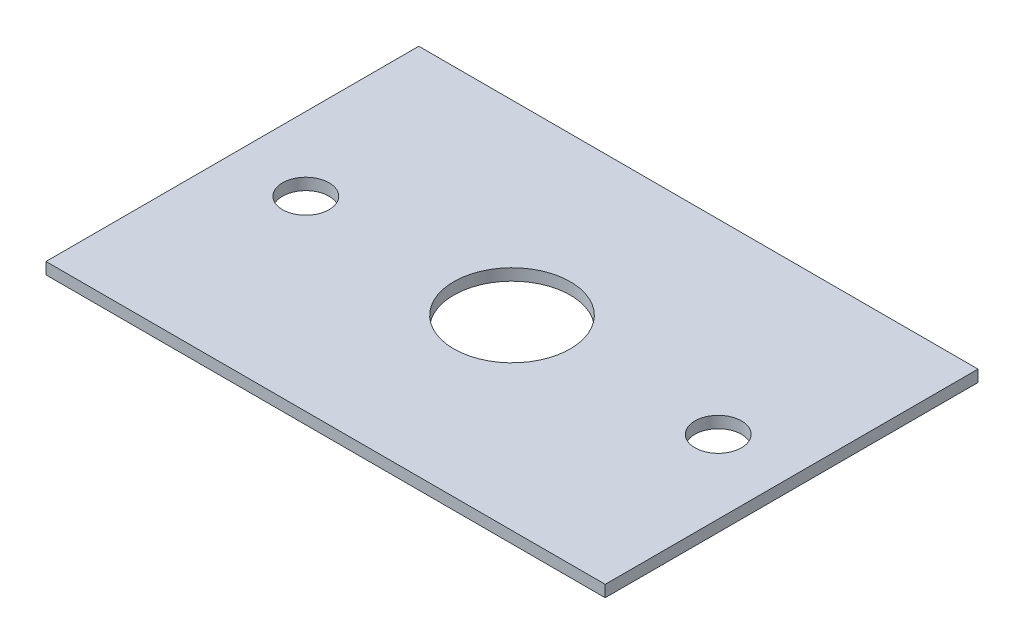
SolidWorks part; units mm, degrees
ref_plane "Front Plane" through (0, 0, 0) normal (0, 0, 1) x (1, 0, 0)
ref_plane "Top Plane" through (0, 0, 0) normal (0, 1, 0) x (1, 0, 0)
ref_plane "Right Plane" through (0, 0, 0) normal (1, 0, 0) x (0, 0, -1)
sketch "Sketch1" plane through (0, 0, 0) normal (0, 1, 0) x (1, 0, 0)
  line L1 (38.1, -25.4) -> (-38.1, -25.4)
  line L2 (38.1, -25.4) -> (38.1, 25.4)
  line L3 (38.1, 25.4) -> (-38.1, 25.4)
  line L4 (-38.1, -25.4) -> (-38.1, 25.4)
  line L5 (38.1, -25.4) -> (-38.1, 25.4) construction
  line L6 (38.1, 25.4) -> (-38.1, -25.4) construction
  circle A0 centre (0, 0) radius 7.9375
  circle A1 centre (-28.1, 0) radius 3.175
  circle A2 centre (28.1, 0) radius 3.175
  point P0 (0, 0)
  point P12 (0, 0)
  dimension "D3" = 15.875
  dimension "D6" = 6.35
  dimension "D7" = 6.35
  dimension "D1" = 50.8
  dimension "D2" = 76.2
  dimension "D4" = 10
  dimension "D5" = 10
extrude "Boss-Extrude1" add sketch "Sketch1" along normal blind 1.5875
equation "\"D7@Sketch1\"=\"D6@Sketch1\""
equation "\"D4@Sketch1\"=\"D5@Sketch1\""
